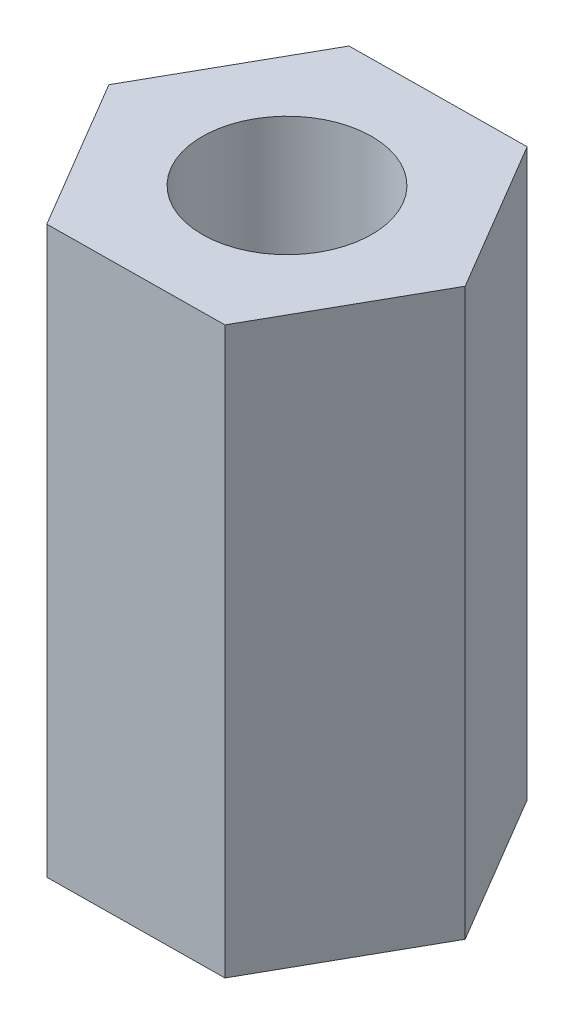
SolidWorks part; units mm, degrees
ref_plane "Front" through (0, 0, 0) normal (0, 0, 1) x (1, 0, 0)
ref_plane "Top" through (0, 0, 0) normal (0, 1, 0) x (1, 0, 0)
ref_plane "Right" through (0, 0, 0) normal (1, 0, 0) x (0, 0, -1)
sketch "Sketch1" plane through (0, 0, 0) normal (0, 1, 0) x (1, 0, 0)
  line L1 (-1.5868, 2.6836) -> (-3.1175, -0.0324)
  line L2 (-3.1175, -0.0324) -> (-1.5307, -2.7161)
  line L3 (-1.5307, -2.7161) -> (1.5868, -2.6836)
  line L4 (1.5868, -2.6836) -> (3.1175, 0.0324)
  line L5 (3.1175, 0.0324) -> (1.5307, 2.7161)
  line L6 (1.5307, 2.7161) -> (-1.5868, 2.6836)
  circle A0 centre (0, 0) radius 2.7 construction
  point P1 (2.3522, -1.3256)
  dimension "D1" = 5.4
extrude "Boss-Extrude1" add sketch "Sketch1" along normal blind 10
sketch "Sketch2" plane through (0, 10, 0) normal (0, 1, 0) x (1, 0, 0)
  point P0 (0, 0)
hole_wizard "Ø3.0mm Dowel Hole1" positions "Sketch3" profile "Sketch4" hole size "Ø3.0" standard "ANSI Metric"
sketch "Sketch3" plane through (0, 10, 0) normal (0, 1, 0) x (1, 0, 0)
  point P0 (0, 0)
sketch "Sketch4" plane through (0, 10, 0) normal (1, 0, 0) x (0, 0, 1)
  line L0 (0, 0) -> (0, 26.3013)
  line L1 (0, 26.3013) -> (1.5, 25.4)
  line L2 (1.5, 25.4) -> (1.5, 0)
  line L5 (1.5, 0) -> (0, 0)
  line L10 (0, 26.3013) -> (-1.5, 25.4) construction
  line L11 (0, -6.35) -> (0, 107.95) construction
  dimension "Hole Dia." = 3
  dimension "Hole Depth" = 25.4
  dimension "Drill Angle" = 118
